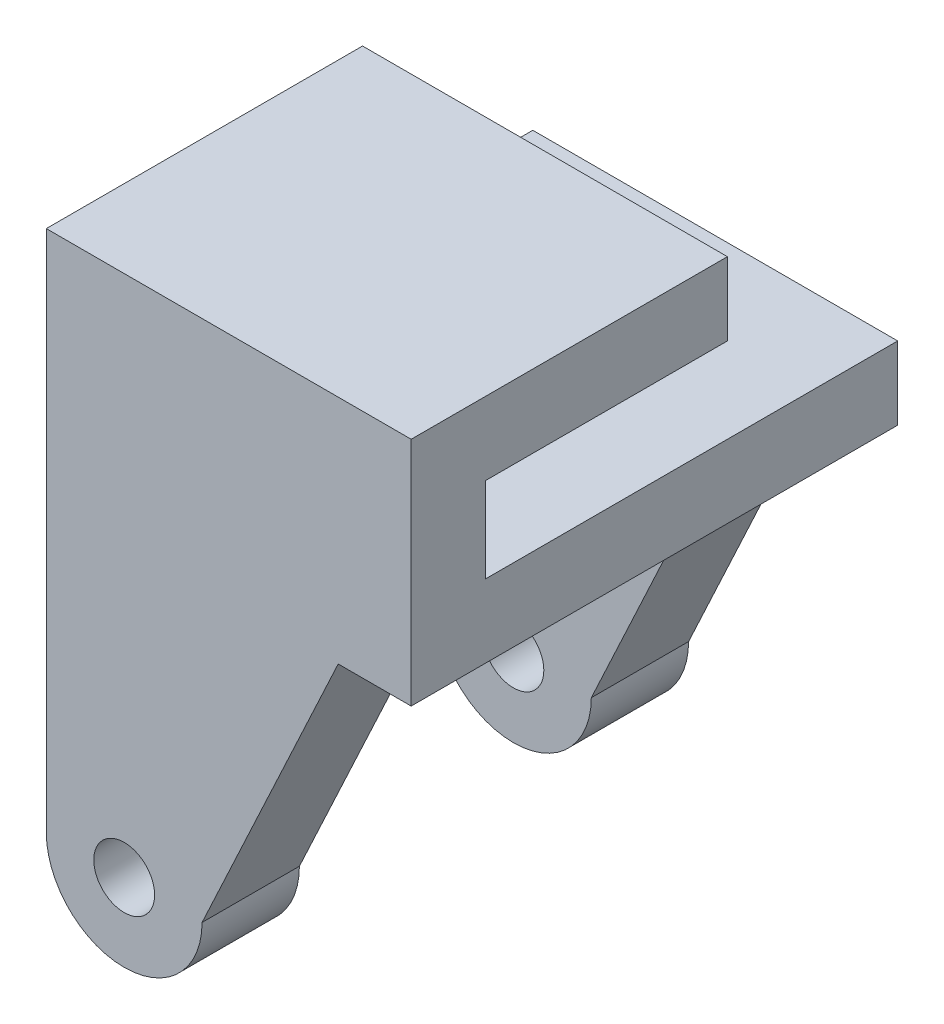
SolidWorks part; units mm, degrees
ref_plane "Front Plane" through (0, 0, 0) normal (0, 0, 1) x (1, 0, 0)
ref_plane "Top Plane" through (0, 0, 0) normal (0, 1, 0) x (1, 0, 0)
ref_plane "Right Plane" through (0, 0, 0) normal (1, 0, 0) x (0, 0, -1)
sketch "Sketch1" plane through (0, 0, 0) normal (1, 0, 0) x (0, 0, -1)
  line L1 (0, 0) -> (20, 0)
  line L2 (0, 0) -> (0, 9.5)
  line L3 (0, 9.5) -> (20, 9.5)
  line L4 (20, 0) -> (20, 9.5)
  dimension "D1" = 9.5
  dimension "D2" = 20
extrude "Boss-Extrude1" add sketch "Sketch1" along normal blind 15 contours L3 L4 L1 L2
sketch "Sketch2" plane through (15, 0, 0) normal (1, 0, 0) x (0, 0, -1)
  line L0 (20, 0) -> (20, 9.5) construction
  line L1 (20, 3) -> (3.0475, 3)
  line L2 (20, 3) -> (20, 6.3375)
  line L3 (13, 6.5) -> (3.0475, 6.5)
  line L4 (3.0475, 3) -> (3.0475, 6.5)
  line L6 (0, 9.5) -> (20, 9.5) construction
  line L9 (13, 6.5) -> (13, 9.5)
  line L10 (13, 9.5) -> (20, 9.5)
  line L11 (20, 6.3375) -> (20, 9.5)
  dimension "D1" = 3.5
  dimension "D2" = 3
  dimension "D3" = 7
extrude "Cut-Extrude1" cut sketch "Sketch2" against normal through all and the other way through all
sketch "Sketch4" plane through (0, 0, 0) normal (0, 0, 1) x (1, 0, 0)
  line L0 (0, 0) -> (0, -12)
  line L1 (12, 0) -> (6.4043, -12)
  line L2 (15, 0) -> (0, 0) construction
  line L3 (0, 0) -> (12, 0)
  arc A0 (0, -12) -> (6.4043, -12) centre (3.2022, -12) ccw
  circle A1 centre (3.2022, -12) radius 1.25
  dimension "D3" = 2.5
  dimension "D4" = 12
  dimension "D1" = 12
  dimension "D2" = 115
extrude "Boss-Extrude3" add sketch "Sketch4" against normal blind 4
ref_plane "Plane1" through (0, 0, -10) normal (0, 0, 1) x (1, 0, 0)
mirror "Mirror1" about plane through (0, 0, -10) normal (0, 0, 1) of "Boss-Extrude3"
